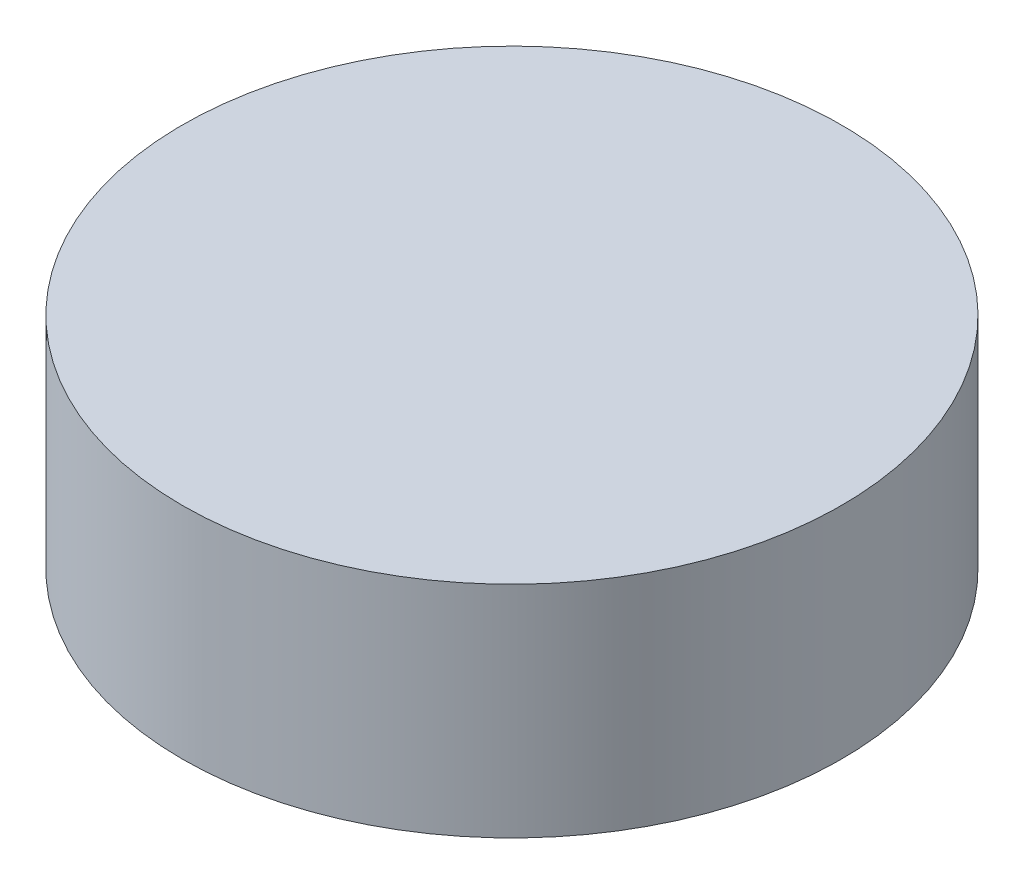
SolidWorks part; units mm, degrees
other "Markup1"
sketch "Sketch2" plane through (-150, 100, 150) normal (-0.3825, 0.8703, 0.3103) x (0.9151, 0.4033, -0.003)
sketch "Sketch3" plane through (-150, 100, 150) normal (-0.3825, 0.8703, 0.3103) x (0.9151, 0.4033, -0.003)
ref_plane "Front Plane" through (0, 0, 0) normal (0, 0, 1) x (1, 0, 0)
ref_plane "Top Plane" through (0, 0, 0) normal (0, 1, 0) x (1, 0, 0)
ref_plane "Right Plane" through (0, 0, 0) normal (1, 0, 0) x (0, 0, -1)
sketch "Sketch1" plane through (0, 0, 0) normal (0, 1, 0) x (1, 0, 0)
  circle A0 centre (0, 0) radius 150
  dimension "D1" = 300
extrude "Boss-Extrude1" add sketch "Sketch1" along normal blind 100
